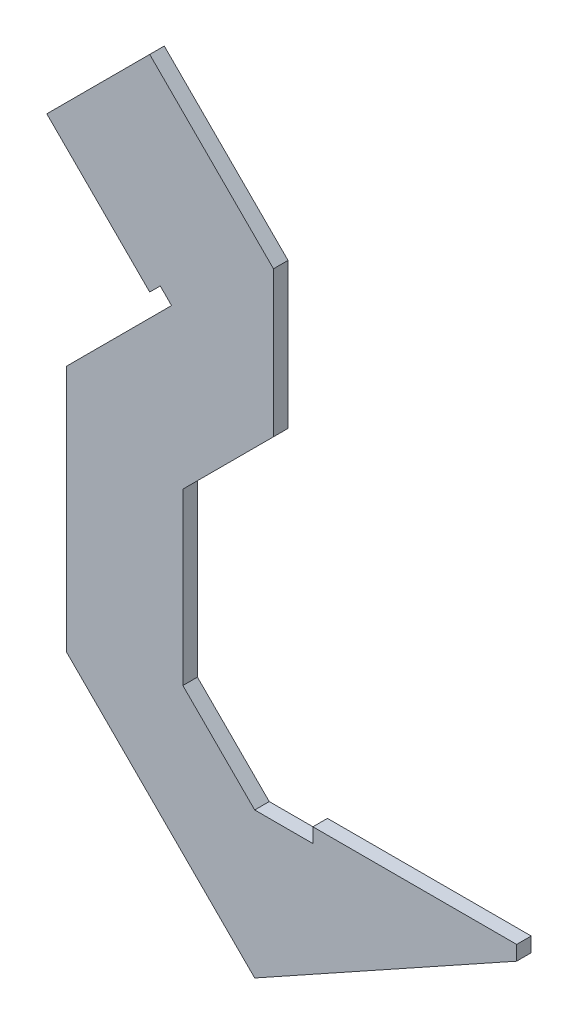
SolidWorks part; units mm, degrees
material "PBT General Purpose"
ref_plane "Front Plane" through (0, 0, 0) normal (0, 0, 1) x (1, 0, 0)
ref_plane "Top Plane" through (0, 0, 0) normal (0, 1, 0) x (1, 0, 0)
ref_plane "Right Plane" through (0, 0, 0) normal (1, 0, 0) x (0, 0, -1)
sketch "Sketch1" plane through (0, 0, 0) normal (0, 0, 1) x (1, 0, 0)
  line L0 (0, 0) -> (-1.4, 0)
  line L1 (-1.4, 0) -> (-1.4, -0.1)
  line L2 (-1.4, -0.1) -> (-1.8, -0.1)
  line L6 (-3.0937, 0.1937) -> (-1.8, -1.1)
  line L7 (-1.8, -1.1) -> (0, -0.1)
  line L8 (0, -0.1) -> (0, 0)
  line L10 (0, 0) -> (0.1, 0) construction
  line L11 (-3.8142, 3.9142) -> (0.1, 0) construction
  line L12 (-1.8, -0.1) -> (-2.2937, 0.3937)
  line L13 (-2.2937, 0.3937) -> (-2.2937, 1.5625)
  line L14 (-2.2937, 1.5625) -> (-1.671, 2.1852)
  line L15 (-1.671, 2.1852) -> (-1.671, 3.1852)
  line L16 (-1.671, 3.1852) -> (-2.5215, 4.0358)
  line L17 (-2.5215, 4.0358) -> (-3.2286, 3.3286)
  line L18 (-3.2286, 3.3286) -> (-2.5215, 2.6215)
  line L19 (-2.5215, 2.6215) -> (-2.449, 2.694)
  line L20 (-2.449, 2.694) -> (-2.3713, 2.6163)
  line L21 (-2.3713, 2.6163) -> (-3.0937, 1.8938)
  line L22 (-3.0937, 1.8938) -> (-3.0937, 0.1937)
  point P3 (-2.1273, 0.3909)
  point P20 (-1.8, -1.1)
  point P21 (-1.8, -1.1)
  point P22 (-1.7674, -1.1572)
  point P23 (-1.7669, -1.0817)
  point P24 (0, 0)
  point P25 (-2.9171, 0.158)
  point P26 (-2.2873, 0.3873)
  point P28 (-1.8832, -1.1)
  point P29 (-1.8, -1.1)
  dimension "D1" = 1.4
  dimension "D2" = 0.1
  dimension "D3" = 0.4
  dimension "D4" = 0.1
  dimension "D5" = 45
  dimension "D6" = 0.1
  dimension "D7" = 0.8
  dimension "D8" = 0.8
  dimension "D9" = 1
  dimension "D10" = 1
  dimension "D11" = 1
  dimension "D12" = 135
  dimension "D13" = 1
extrude "Boss-Extrude1" add sketch "Sketch1" along normal mid plane 0.1 contours L6 L7 L8 L0 L1 L2 L12 L13 L14 L15 L16 L17 L18 L19 L20 L21 L22
